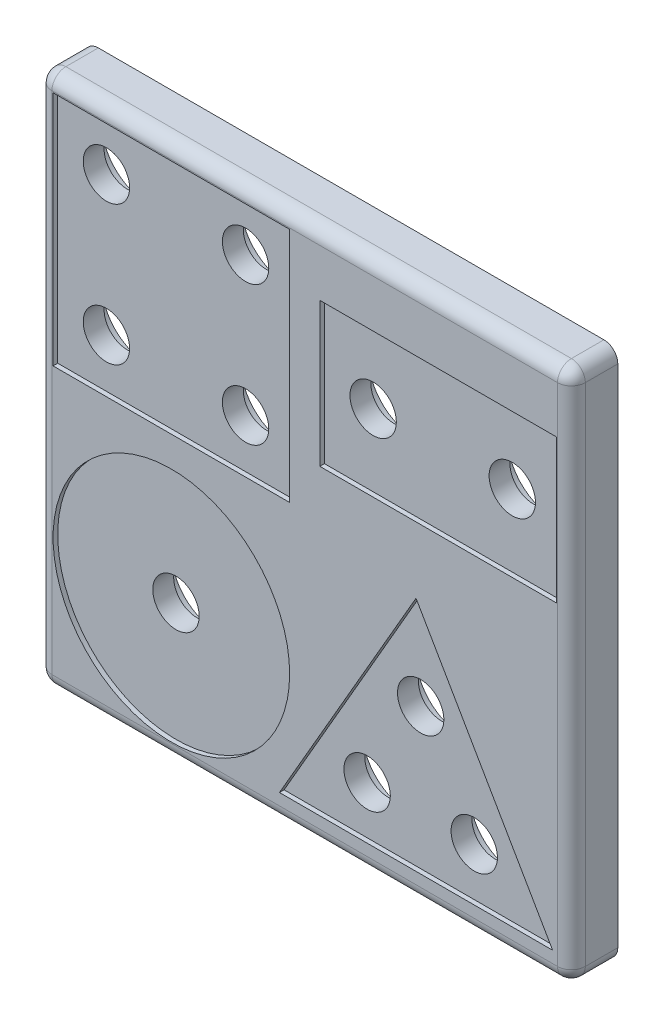
SolidWorks part; units mm, degrees
ref_plane "Front Plane" through (0, 0, 0) normal (0, 0, 1) x (1, 0, 0)
ref_plane "Top Plane" through (0, 0, 0) normal (0, 1, 0) x (1, 0, 0)
ref_plane "Right Plane" through (0, 0, 0) normal (1, 0, 0) x (0, 0, -1)
sketch "Sketch1" plane through (0, 0, 0) normal (0, 0, 1) x (1, 0, 0)
  line L1 (57.5, 57.5) -> (-57.5, 57.5)
  line L2 (57.5, 57.5) -> (57.5, -57.5)
  line L3 (57.5, -57.5) -> (-57.5, -57.5)
  line L4 (-57.5, 57.5) -> (-57.5, -57.5)
  line L5 (57.5, 57.5) -> (-57.5, -57.5) construction
  line L6 (57.5, -57.5) -> (-57.5, 57.5) construction
  point P0 (0, 0)
  dimension "D1" = 115
  dimension "D2" = 115
extrude "Boss-Extrude1" add sketch "Sketch1" along normal blind 10
sketch "Sketch2" plane through (0, 0, 10) normal (0, 0, 1) x (1, 0, 0)
  line L0 (-57.5, 57.5) -> (0, 0) construction
  line L1 (0, 0) -> (-57.5, 0)
  line L2 (0, 0) -> (0, 57.5)
  line L3 (0, 57.5) -> (-57.5, 57.5)
  line L4 (-57.5, 0) -> (-57.5, 57.5)
  line L5 (0, 57.5) -> (-57.5, 0) construction
  line L7 (-3.25, 54.25) -> (-54.25, 54.25)
  line L8 (-3.25, 54.25) -> (-3.25, 3.25)
  line L9 (-3.25, 3.25) -> (-54.25, 3.25)
  line L10 (-54.25, 54.25) -> (-54.25, 3.25)
  line L11 (-3.25, 54.25) -> (-54.25, 3.25) construction
  line L12 (-3.25, 3.25) -> (-54.25, 54.25) construction
  point P6 (-28.75, 28.75)
  dimension "D1" = 57.5
  dimension "D2" = 51
extrude "Cut-Extrude1" cut sketch "Sketch2" against normal blind 1 contours L8 L7 L10 L9
sketch "Sketch3" plane through (0, 0, 9) normal (0, 0, 1) x (1, 0, 0)
  line L0 (-54.25, 54.25) -> (-3.25, 3.25) construction
  line L1 (-3.25, 3.25) -> (-3.25, 54.25)
  line L2 (-3.25, 54.25) -> (-54.25, 3.25) construction
  line L4 (-43.75, 13.75) -> (-13.75, 13.75) construction
  line L5 (-43.75, 13.75) -> (-43.75, 43.75) construction
  line L6 (-43.75, 43.75) -> (-13.75, 43.75) construction
  line L7 (-13.75, 13.75) -> (-13.75, 43.75) construction
  line L8 (-43.75, 13.75) -> (-13.75, 43.75) construction
  line L9 (-43.75, 43.75) -> (-13.75, 13.75) construction
  line L10 (-3.75, 53.75) -> (-53.75, 53.75) construction
  line L11 (-3.75, 53.75) -> (-3.75, 3.75) construction
  line L12 (-3.75, 3.75) -> (-53.75, 3.75) construction
  line L13 (-53.75, 53.75) -> (-53.75, 3.75) construction
  line L14 (-3.75, 53.75) -> (-53.75, 3.75) construction
  line L15 (-3.75, 3.75) -> (-53.75, 53.75) construction
  circle A0 centre (-43.75, 43.75) radius 4.5 construction
  circle A1 centre (-13.75, 43.75) radius 4.5 construction
  circle A2 centre (-13.75, 13.75) radius 4.5 construction
  circle A3 centre (-43.75, 13.75) radius 4.5 construction
  circle A4 centre (-43.75, 43.75) radius 5
  circle A5 centre (-13.75, 43.75) radius 5
  circle A6 centre (-13.75, 13.75) radius 5
  circle A7 centre (-43.75, 13.75) radius 5
  point P4 (-28.75, 28.75)
  point P21 (-28.75, 28.75)
  dimension "D2" = 9
  dimension "D3" = 9
  dimension "D4" = 9
  dimension "D5" = 9
  dimension "D6" = 10
  dimension "D7" = 10
  dimension "D8" = 10
  dimension "D9" = 10
  dimension "D1" = 30
  dimension "D10" = 50
sketch "Sketch4" plane through (0, 0, 10) normal (0, 0, 1) x (1, 0, 0)
  line L0 (0, 57.5) -> (57.5, 0) construction
  line L1 (0, 0) -> (57.5, 0) construction
  line L2 (0, 0) -> (0, 57.5) construction
  line L3 (0, 57.5) -> (57.5, 57.5) construction
  line L4 (57.5, 0) -> (57.5, 57.5) construction
  line L5 (57.5, 0) -> (0, 0)
  line L6 (0, 0) -> (57.5, 57.5) construction
  line L8 (54.25, 13.25) -> (3.25, 13.25)
  line L9 (54.25, 13.25) -> (54.25, 44.25)
  line L10 (54.25, 44.25) -> (3.25, 44.25)
  line L11 (3.25, 13.25) -> (3.25, 44.25)
  line L12 (54.25, 13.25) -> (3.25, 44.25) construction
  line L13 (54.25, 44.25) -> (3.25, 13.25) construction
  point P6 (28.75, 28.75)
  dimension "D1" = 51
  dimension "D2" = 31
extrude "Cut-Extrude2" cut sketch "Sketch4" against normal blind 1 contours L11 L8 L9 L10
sketch "Sketch5" plane through (0, 0, 9) normal (0, 0, 1) x (1, 0, 0)
  line L0 (3.25, 44.25) -> (54.25, 13.25) construction
  line L1 (54.25, 13.25) -> (54.25, 44.25)
  line L2 (54.25, 44.25) -> (3.25, 13.25) construction
  line L3 (-0.6858, 28.75) -> (59.8973, 28.75) construction
  line L4 (53.75, 13.5539) -> (3.75, 13.5539) construction
  line L5 (53.75, 13.5539) -> (53.75, 43.9461) construction
  line L6 (53.75, 43.9461) -> (3.75, 43.9461) construction
  line L7 (3.75, 13.5539) -> (3.75, 43.9461) construction
  line L8 (53.75, 13.5539) -> (3.75, 43.9461) construction
  line L9 (53.75, 43.9461) -> (3.75, 13.5539) construction
  circle A0 centre (13.75, 28.75) radius 4.5 construction
  circle A1 centre (43.75, 28.75) radius 4.5 construction
  circle A2 centre (13.75, 28.75) radius 5
  circle A3 centre (43.75, 28.75) radius 5
  point P4 (28.75, 28.75)
  dimension "D3" = 9
  dimension "D4" = 9
  dimension "D7" = 10
  dimension "D8" = 10
  dimension "D1" = 50
  dimension "D2" = 30.3922
  dimension "D5" = 15
  dimension "D6" = 15
sketch "Sketch11" plane through (0, 0, 10) normal (0, 0, 1) x (1, 0, 0)
  line L0 (-57.5, 0) -> (0, -57.5) construction
  line L1 (0, 0) -> (-57.5, 0) construction
  line L2 (0, 0) -> (0, -57.5) construction
  line L3 (0, -57.5) -> (-57.5, -57.5) construction
  line L4 (-57.5, 0) -> (-57.5, -57.5) construction
  line L5 (0, -57.5) -> (0, 0)
  line L6 (0, 0) -> (-57.5, -57.5) construction
  circle A0 centre (-28.75, -28.75) radius 5
  circle A1 centre (-28.75, -28.75) radius 4.5 construction
  circle A2 centre (-28.75, -28.75) radius 25.5
  dimension "D1" = 9
  dimension "D2" = 10
  dimension "D3" = 51
extrude "Cut-Extrude8" cut sketch "Sketch11" against normal blind 1 contours A2 A0
sketch "Sketch6" plane through (0, 0, 10) normal (0, 0, 1) x (1, 0, 0)
  line L0 (24, -35) -> (24, -1) construction
  line L1 (0, 0) -> (57.5, 0) construction
  line L2 (0, 0) -> (0, -57.5) construction
  line L3 (0, -57.5) -> (57.5, -57.5) construction
  line L4 (57.5, 0) -> (57.5, -57.5) construction
  line L5 (24, -1) -> (-5.4449, -52)
  line L6 (-5.4449, -52) -> (53.4449, -52)
  line L7 (53.4449, -52) -> (24, -1)
  line L8 (24, -21.6667) -> (12.453, -41.6667) construction
  line L9 (12.453, -41.6667) -> (35.547, -41.6667) construction
  line L10 (35.547, -41.6667) -> (24, -21.6667) construction
  circle A0 centre (24, -35) radius 17 construction
  circle A1 centre (24, -35) radius 6.6667 construction
  circle A2 centre (24, -21.6667) radius 4.5 construction
  circle A3 centre (35.547, -41.6667) radius 4.5 construction
  circle A4 centre (12.453, -41.6667) radius 4.5 construction
  circle A5 centre (24, -21.6667) radius 5
  circle A6 centre (35.547, -41.6667) radius 5
  circle A7 centre (12.453, -41.6667) radius 5
  dimension "D5" = 9
  dimension "D6" = 9
  dimension "D7" = 9
  dimension "D8" = 10
  dimension "D9" = 10
  dimension "D10" = 10
  dimension "D1" = 51
  dimension "D2" = 35
  dimension "D3" = 24
  dimension "D4" = 20
extrude "Cut-Extrude9" cut sketch "Sketch6" against normal blind 1
sketch "Sketch17" plane through (0, 0, 0) normal (0, 0, 1) x (1, 0, 0)
  line L1 (-57.75, 57.75) -> (57.75, 57.75) construction
  line L2 (-57.75, 57.75) -> (-57.75, -57.75) construction
  line L3 (-57.75, -57.75) -> (57.75, -57.75) construction
  line L4 (57.75, 57.75) -> (57.75, -57.75) construction
  line L5 (-57.75, 57.75) -> (57.75, -57.75) construction
  line L6 (-57.75, -57.75) -> (57.75, 57.75) construction
  point P0 (0, 0)
  dimension "D1" = 115.5
  dimension "D2" = 115.5
extrude "Cut-Extrude10" cut sketch "Sketch3" against normal blind 10 contours A4 | A5 | A6 | A7
extrude "Cut-Extrude11" cut sketch "Sketch5" against normal blind 10 contours A2 | A3
sketch "Sketch19" plane through (0, 0, 10) normal (0, 0, 1) x (1, 0, 0)
  circle A0 centre (-28.75, -28.75) radius 5
extrude "Cut-Extrude12" cut sketch "Sketch19" against normal blind 10
sketch "Sketch20" plane through (0, 0, 10) normal (0, 0, 1) x (1, 0, 0)
  circle A0 centre (24, -21.6667) radius 5
  circle A1 centre (35.547, -41.6667) radius 5
  circle A2 centre (12.453, -41.6667) radius 5
  dimension "D1" = 10
  dimension "D2" = 10
  dimension "D3" = 10
extrude "Cut-Extrude13" cut sketch "Sketch20" against normal blind 10
sketch "Sketch21" plane through (0, 0, 0) normal (0, 0, -1) x (-1, 0, 0)
  line L0 (57.5, 0) -> (0, -57.5) construction
  line L1 (-24, -21.6667) -> (-12.453, -41.6667) construction
  line L2 (-12.453, -41.6667) -> (-35.547, -41.6667) construction
  circle A0 centre (-43.75, 28.75) radius 10
  circle A1 centre (-13.75, 28.75) radius 10
  circle A2 centre (13.75, 43.75) radius 10
  circle A3 centre (43.75, 43.75) radius 10
  circle A4 centre (43.75, 13.75) radius 10
  circle A5 centre (13.75, 13.75) radius 10
  circle A6 centre (-24, -21.6667) radius 10
  circle A7 centre (28.75, -28.75) radius 10
  circle A8 centre (-12.453, -41.6667) radius 10
  circle A9 centre (-35.547, -41.6667) radius 10
  dimension "D1" = 20
  dimension "D2" = 20
  dimension "D3" = 20
  dimension "D4" = 20
  dimension "D5" = 20
  dimension "D6" = 20
  dimension "D7" = 20
  dimension "D8" = 20
  dimension "D9" = 20
  dimension "D10" = 20
extrude "Cut-Extrude14" cut sketch "Sketch21" against normal blind 4.5
fillet "Fillet2" radius 3 8 edges at (57.5, 57.5, 5) (0, 57.5, 10) (-57.5, 57.5, 5) (-57.5, 0, 10) (-57.5, -57.5, 5) (57.5, -57.5, 5) (0, -57.5, 10) (57.5, 0, 10)
